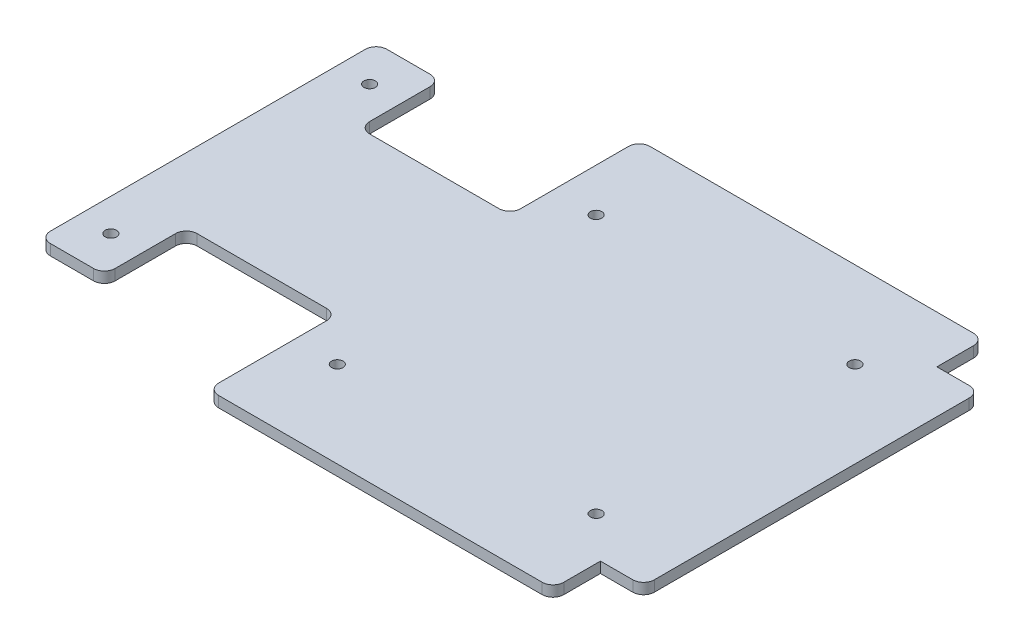
SolidWorks part; units mm, degrees
ref_plane "Front Plane" through (0, 0, 0) normal (0, 0, 1) x (1, 0, 0)
ref_plane "Top Plane" through (0, 0, 0) normal (0, 1, 0) x (1, 0, 0)
ref_plane "Right Plane" through (0, 0, 0) normal (1, 0, 0) x (0, 0, -1)
sketch "Sketch1" plane through (0, 0, 0) normal (0, 1, 0) x (1, 0, 0)
  line L0 (-222.25, 99.06) -> (-196.85, 99.06)
  line L1 (95.25, -127) -> (-95.25, -127)
  line L2 (101.6, -120.65) -> (101.6, -99.06)
  line L3 (95.25, 127) -> (-95.25, 127)
  line L4 (-101.6, -120.65) -> (-101.6, -57.15)
  line L5 (101.6, -127) -> (-101.6, 127) construction
  line L6 (101.6, 127) -> (-101.6, -127) construction
  line L7 (-190.5, 92.71) -> (-190.5, 57.15)
  line L8 (-184.15, 50.8) -> (-107.95, 50.8)
  line L9 (-228.6, -127) -> (-228.6, 127) construction
  line L10 (-228.6, -127) -> (-228.6, 127) construction
  line L11 (0, 0) -> (-318.3038, 0) construction
  line L12 (-228.6, 92.71) -> (-228.6, -92.71)
  line L13 (-222.25, -99.06) -> (-196.85, -99.06)
  line L14 (-190.5, -92.71) -> (-190.5, -57.15)
  line L15 (-184.15, -50.8) -> (-107.95, -50.8)
  line L16 (-101.6, 57.15) -> (-101.6, 120.65)
  line L17 (127, -127) -> (127, 127) construction
  line L18 (127, -92.71) -> (127, 92.71)
  line L19 (101.6, 99.06) -> (120.65, 99.06)
  line L20 (101.6, -99.06) -> (120.65, -99.06)
  line L21 (101.6, 99.06) -> (101.6, 120.65)
  arc A0 (-222.25, -99.06) -> (-228.6, -92.71) centre (-222.25, -92.71) cw
  arc A1 (-196.85, -99.06) -> (-190.5, -92.71) centre (-196.85, -92.71) ccw
  arc A2 (-190.5, -57.15) -> (-184.15, -50.8) centre (-184.15, -57.15) cw
  arc A3 (-107.95, -50.8) -> (-101.6, -57.15) centre (-107.95, -57.15) cw
  arc A4 (-95.25, -127) -> (-101.6, -120.65) centre (-95.25, -120.65) cw
  arc A5 (95.25, -127) -> (101.6, -120.65) centre (95.25, -120.65) ccw
  arc A6 (101.6, 120.65) -> (95.25, 127) centre (95.25, 120.65) ccw
  arc A7 (-95.25, 127) -> (-101.6, 120.65) centre (-95.25, 120.65) ccw
  arc A8 (-107.95, 50.8) -> (-101.6, 57.15) centre (-107.95, 57.15) ccw
  arc A9 (-190.5, 57.15) -> (-184.15, 50.8) centre (-184.15, 57.15) ccw
  arc A10 (-196.85, 99.06) -> (-190.5, 92.71) centre (-196.85, 92.71) cw
  arc A11 (-222.25, 99.06) -> (-228.6, 92.71) centre (-222.25, 92.71) ccw
  arc A12 (120.65, 99.06) -> (127, 92.71) centre (120.65, 92.71) cw
  arc A13 (120.65, -99.06) -> (127, -92.71) centre (120.65, -92.71) ccw
  point P0 (0, 0)
  point P16 (-228.6, 0)
  point P21 (-228.6, -99.06)
  point P24 (-190.5, -99.06)
  point P27 (-190.5, -50.8)
  point P30 (-101.6, -50.8)
  point P45 (-101.6, 50.8)
  point P48 (-190.5, 50.8)
  point P51 (-190.5, 99.06)
  point P54 (-228.6, 99.06)
  point P63 (127, 99.06)
  point P66 (127, -99.06)
  dimension "D6" = 6.35
  dimension "D7" = 6.35
  dimension "D1" = 203.2
  dimension "D2" = 254
  dimension "D3" = 50.8
  dimension "D4" = 88.9
  dimension "D5" = 99.06
extrude "Boss-Extrude1" add sketch "Sketch1" along normal blind 6.35
sketch "Sketch2" plane through (0, 6.35, 0) normal (0, 1, 0) x (1, 0, 0)
  line L0 (-228.6, 0) -> (101.6, 0) construction
  line L2 (-228.6, 92.71) -> (-228.6, -92.71) construction
  line L4 (-101.6, -57.15) -> (-101.6, -120.65) construction
  line L5 (101.6, -120.65) -> (101.6, -99.06) construction
  circle A0 centre (-76.2, 76.2) radius 3.3655
  circle A1 centre (76.2, 76.2) radius 3.3655
  circle A2 centre (-76.2, -76.2) radius 3.3655
  circle A3 centre (76.2, -76.2) radius 3.3655
  circle A4 centre (-209.55, 76.2) radius 3.3655
  circle A5 centre (-209.55, -76.2) radius 3.3655
  point P4 (0, 0)
  point P5 (0, 0)
  point P23 (0, 0)
  dimension "D1" = 6.731
  dimension "D3" = 25.4
  dimension "D4" = 152.4
  dimension "D2" = 25.4
  dimension "D5" = 19.05
extrude "Cut-Extrude1" cut sketch "Sketch2" against normal through all
